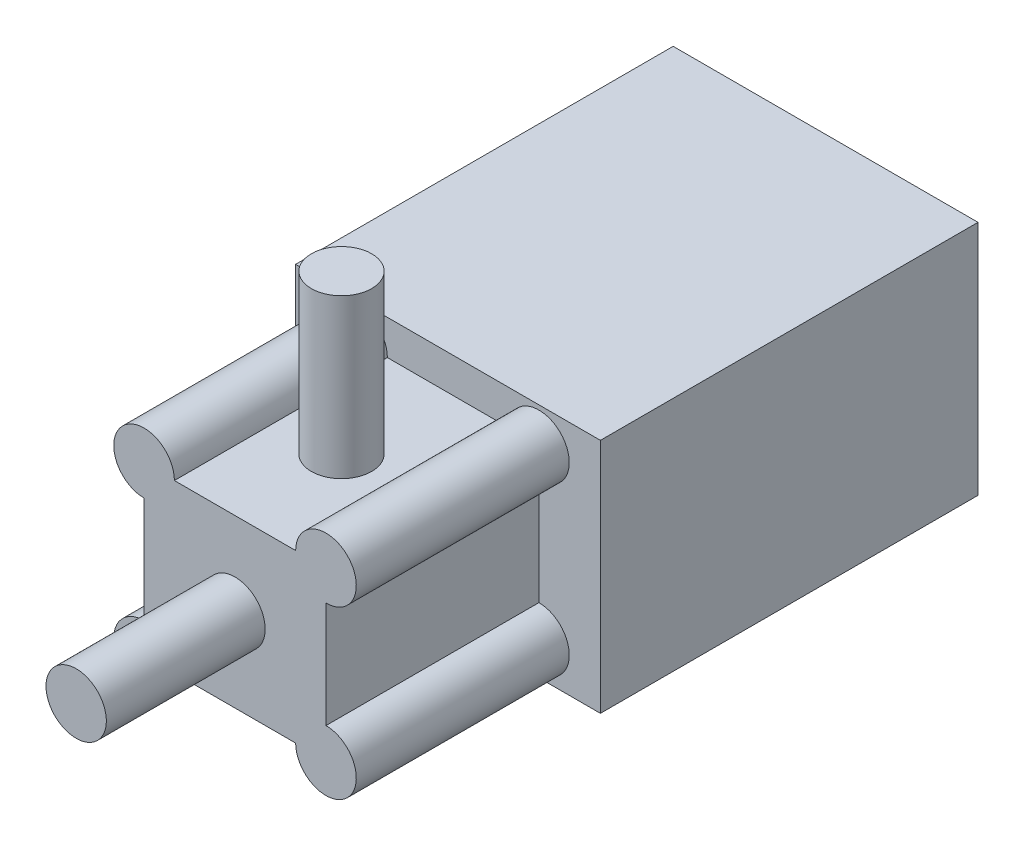
SolidWorks part; units mm, degrees
ref_plane "Front Plane" through (0, 0, 0) normal (0, 0, 1) x (1, 0, 0)
ref_plane "Top Plane" through (0, 0, 0) normal (0, 1, 0) x (1, 0, 0)
ref_plane "Right Plane" through (0, 0, 0) normal (1, 0, 0) x (0, 0, -1)
sketch "Sketch1" plane through (0, 0, 0) normal (0, 0, 1) x (1, 0, 0)
  line L1 (10.055, -7.8) -> (-10.055, -7.8)
  line L2 (10.055, -7.8) -> (10.055, 7.8)
  line L3 (10.055, 7.8) -> (-10.055, 7.8)
  line L4 (-10.055, -7.8) -> (-10.055, 7.8)
  line L5 (10.055, -7.8) -> (-10.055, 7.8) construction
  line L6 (10.055, 7.8) -> (-10.055, -7.8) construction
  point P0 (0, 0)
  dimension "D1" = 15.6
  dimension "D2" = 20.11
extrude "Boss-Extrude1" add sketch "Sketch1" along normal blind 24.91
sketch "Sketch2" plane through (0, 0, 24.91) normal (0, 0, 1) x (1, 0, 0)
  line L1 (6, -5.5) -> (-6, -5.5)
  line L2 (6, -5.5) -> (6, 5.5)
  line L3 (6, 5.5) -> (-6, 5.5)
  line L4 (-6, -5.5) -> (-6, 5.5)
  line L5 (6, -5.5) -> (-6, 5.5) construction
  line L6 (6, 5.5) -> (-6, -5.5) construction
  circle A0 centre (-6, 5.5) radius 2
  circle A1 centre (6, 5.5) radius 2
  circle A2 centre (6, -5.5) radius 2
  circle A3 centre (-6, -5.5) radius 2
  point P0 (0, 0)
  dimension "D3" = 4
  dimension "D1" = 11
  dimension "D4" = 4
  dimension "D5" = 4
  dimension "D6" = 4
  dimension "D2" = 12
extrude "Boss-Extrude2" add sketch "Sketch2" along normal blind 14.05 contours L3 A0 L4 | A3 L1 A2 L2 A1 L3 A0 L4 | L2 A1 L3 | L1 A2 L2 | L2 A2 L1 | L4 A3 L1 | L1 A3 L4 | L3 A1 L2 | L4 A0 L3
sketch "Sketch3" plane through (0, 5.5, 0) normal (0, 1, 0) x (1, 0, 0)
  line L0 (-4, -31.935) -> (4, -31.935) construction
  line L1 (-4, -24.91) -> (4, -24.91) construction
  line L2 (-4, -24.91) -> (-4, -38.96) construction
  line L3 (-4, -38.96) -> (4, -38.96) construction
  line L4 (4, -24.91) -> (4, -38.96) construction
  line L5 (0, -24.91) -> (0, -38.96) construction
  circle A0 centre (0, -31.935) radius 1.99
  dimension "D1" = 3.98
extrude "Boss-Extrude3" add sketch "Sketch3" along normal blind 10.45
sketch "Sketch4" plane through (0, 0, 38.96) normal (0, 0, 1) x (1, 0, 0)
  line L1 (6, -5.5) -> (-6, -5.5) construction
  line L2 (6, -5.5) -> (6, 5.5) construction
  line L3 (6, 5.5) -> (-6, 5.5) construction
  line L4 (-6, -5.5) -> (-6, 5.5) construction
  line L5 (6, -5.5) -> (-6, 5.5) construction
  line L6 (6, 5.5) -> (-6, -5.5) construction
  circle A0 centre (0, 0) radius 1.99
  point P0 (0, 0)
  dimension "D1" = 3.98
extrude "Boss-Extrude4" add sketch "Sketch4" along normal blind 10.48
ref_plane "Plane1" through (0, 10.725, 0) normal (0, 1, 0) x (1, 0, 0)
